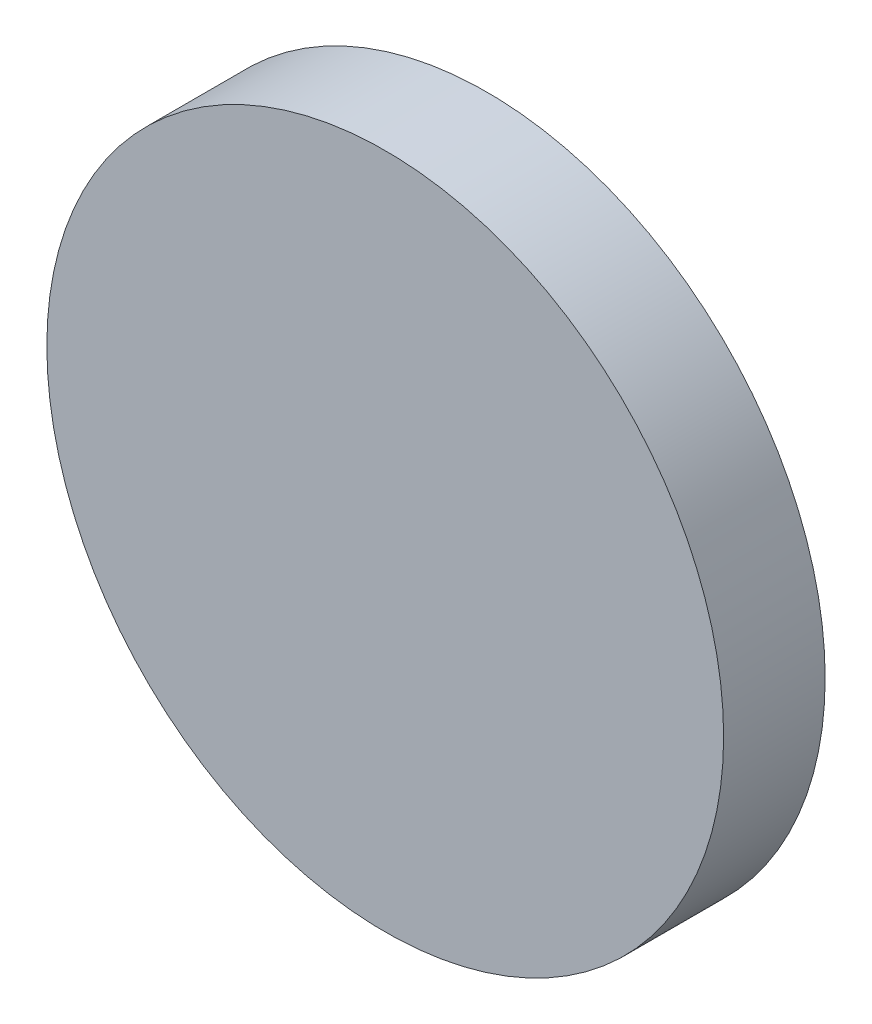
SolidWorks part; units mm, degrees
ref_plane "Přední rovina" through (0, 0, 0) normal (0, 0, 1) x (1, 0, 0)
ref_plane "Horní rovina" through (0, 0, 0) normal (0, 1, 0) x (1, 0, 0)
ref_plane "Pravá rovina" through (0, 0, 0) normal (1, 0, 0) x (0, 0, -1)
sketch "Sketch1" plane through (0, 0, 0) normal (0, 1, 0) x (1, 0, 0)
  line L1 (-50, 0) -> (-40, 0)
  line L2 (-50, 0) -> (-50, -15)
  line L3 (-50, -15) -> (0, -15)
  line L6 (-40, 0) -> (-40, -10)
  line L7 (-40, -10) -> (0, -10)
  line L9 (0, 0) -> (0, -15) construction
  line L13 (0, -15) -> (0, -10)
  point P3 (0, -10)
  dimension "D1" = 50
  dimension "D2" = 10
  dimension "D3" = 10
  dimension "D4" = 5
revolve "Revolve1" add sketch "Sketch1" angle 360 about L9
